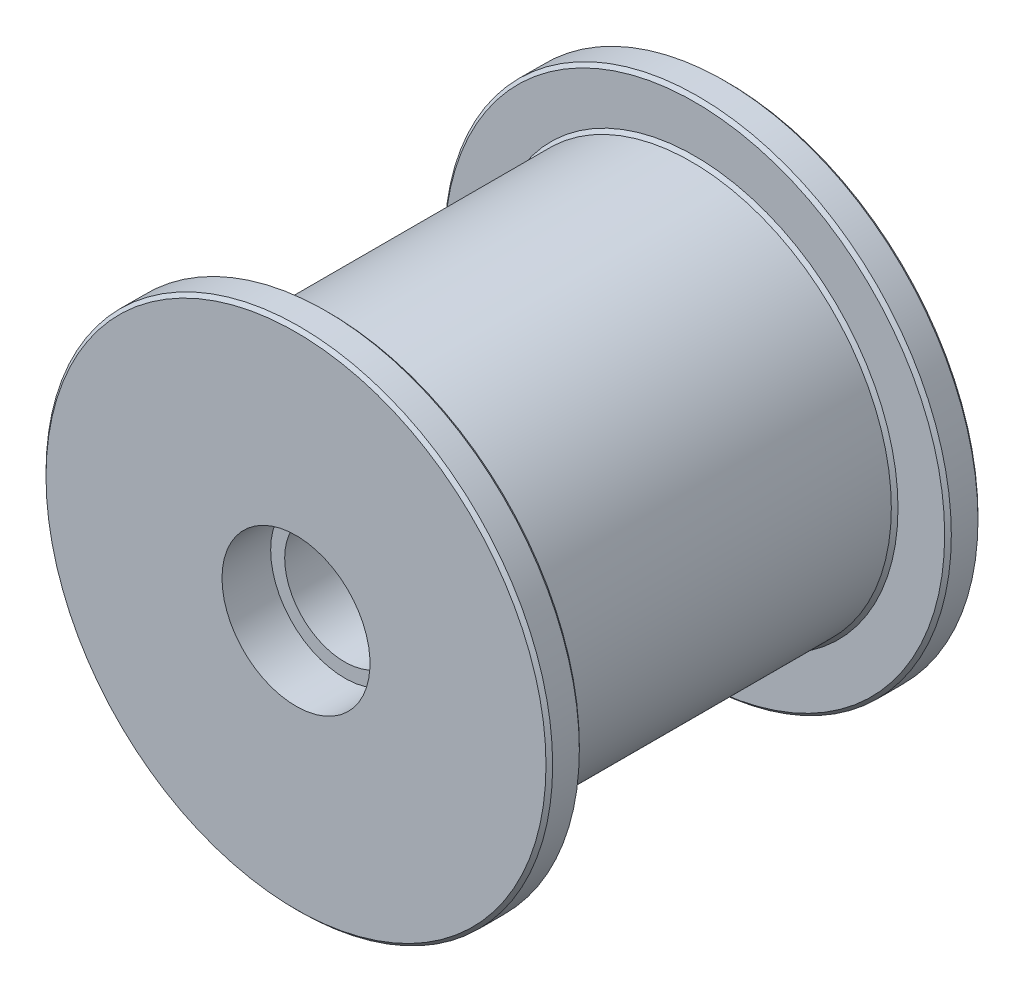
SolidWorks part; units mm, degrees
ref_plane "Front Plane" through (0, 0, 0) normal (0, 0, 1) x (1, 0, 0)
ref_plane "Top Plane" through (0, 0, 0) normal (0, 1, 0) x (1, 0, 0)
ref_plane "Right Plane" through (0, 0, 0) normal (1, 0, 0) x (0, 0, -1)
sketch "Sketch1" plane through (0, 0, 0) normal (0, 1, 0) x (1, 0, 0)
  line L0 (0, 0) -> (0, 64.8)
  line L3 (0, 64.8) -> (-38, 64.8)
  line L4 (-30, 5) -> (-38, 5)
  line L5 (-38, 5) -> (-38, 0)
  line L6 (-30, 59.8) -> (-30, 5)
  line L7 (-30, 59.8) -> (-38, 59.8)
  line L8 (-38, 59.8) -> (-38, 64.8)
  line L9 (-38, 0) -> (0, 0)
  line L10 (-38, 59.8) -> (-38, 5) construction
  dimension "D1" = 54.8
  dimension "D2" = 8
  dimension "D3" = 5
  dimension "D7" = 30
revolve "Revolve1" add sketch "Sketch1" angle 360 about L0
sketch "Sketch7" plane through (0, 0, 0) normal (0, 1, 0) x (1, 0, 0)
  line L0 (0, 0) -> (0, 64.211) construction
  line L1 (0, 64.8) -> (-11.1, 64.8)
  line L2 (-11.1, 64.8) -> (-11.1, 57.5)
  line L3 (-11.1, 57.5) -> (-9, 57.5)
  line L4 (-9, 57.5) -> (-9, 7.3)
  line L5 (-9, 7.3) -> (-11.1, 7.3)
  line L6 (-11.1, 7.3) -> (-11.1, 0)
  line L7 (-11.1, 0) -> (0, 0)
  line L8 (-11.1, 57.5) -> (-11.1, 7.3) construction
  line L9 (-38, 0) -> (38, 0) construction
  line L10 (38, 64.8) -> (-38, 64.8) construction
  line L11 (0, 64.8) -> (0, 0)
  dimension "D1" = 11.1
  dimension "D2" = 9
  dimension "D3" = 7.3
  dimension "D4" = 7.3
revolve "Cut-Revolve1" cut sketch "Sketch7" angle 360 about L11
ref_plane "Plane1" through (0, 0, -32.4) normal (0, 0, 1) x (1, 0, 0)
chamfer "Chamfer1" distance 0.5 angle 45 6 edges at (38, 0, 0) (38, 0, -5) (30, 0, -5) (30, 0, -59.8) (38, 0, -59.8) (38, 0, -64.8)
